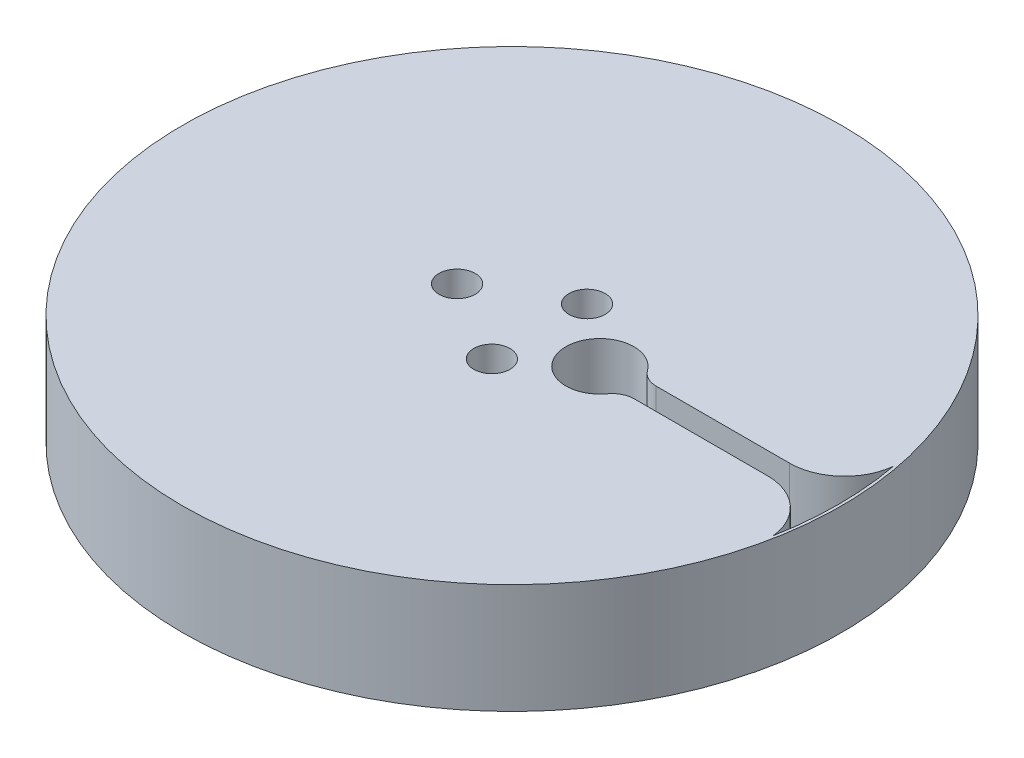
SolidWorks part; units mm, degrees
ref_plane "前视基准面" through (0, 0, 0) normal (0, 0, 1) x (1, 0, 0)
ref_plane "上视基准面" through (0, 0, 0) normal (0, 1, 0) x (1, 0, 0)
ref_plane "右视基准面" through (0, 0, 0) normal (1, 0, 0) x (0, 0, -1)
other "Configuration Table"
sketch "草图1" plane through (0, 0, 0) normal (0, 1, 0) x (1, 0, 0)
  circle A0 centre (0, 0) radius 30
  dimension "D1" = 60
extrude "凸台-拉伸1" add sketch "草图1" along normal blind 10
sketch "草图2" plane through (0, 0, 0) normal (0, -1, 0) x (1, 0, 0)
  line L1 (10.9343, 1) -> (30.9343, 1)
  line L2 (10.9343, 1) -> (10.9343, -1) construction
  line L3 (10.9343, -1) -> (30.9343, -1)
  line L4 (30.9343, 1) -> (30.9343, -1)
  arc A0 (10.9343, 1) -> (10.9343, -1) centre (8, 0) ccw
  dimension "D1" = 6.2
  dimension "D2" = 8
  dimension "D3" = 2
  dimension "D4" = 20
extrude "切除-拉伸1" cut sketch "草图2" against normal blind 10
fillet "圆角1" radius 2 2 edges at (10.9343, 5, -1) (10.9343, 5, 1)
fillet "圆角2" radius 5 2 edges at (29.9833, 5, -1) (29.9833, 5, 1)
sketch "草图3" plane through (0, 0, 0) normal (0, -1, 0) x (1, 0, 0)
  circle A0 centre (0, 0) radius 5 construction
  circle A1 centre (-5, 0) radius 1.65
  circle A2 centre (2.5, 4.3301) radius 1.65
  circle A3 centre (2.5, -4.3301) radius 1.65
  point P15 (0, 0)
  dimension "D1" = 10
  dimension "D2" = 3.3
  dimension "D3" = 3
extrude "切除-拉伸2" cut sketch "草图3" against normal blind 10
sketch "草图4" plane through (0, 0, 0) normal (0, -1, 0) x (1, 0, 0)
  circle A0 centre (0, 0) radius 30
  circle A1 centre (0, 0) radius 29.75
  dimension "D1" = 60
  dimension "D2" = 59.5
extrude "凸台-拉伸2" add sketch "草图4" against normal blind 10
